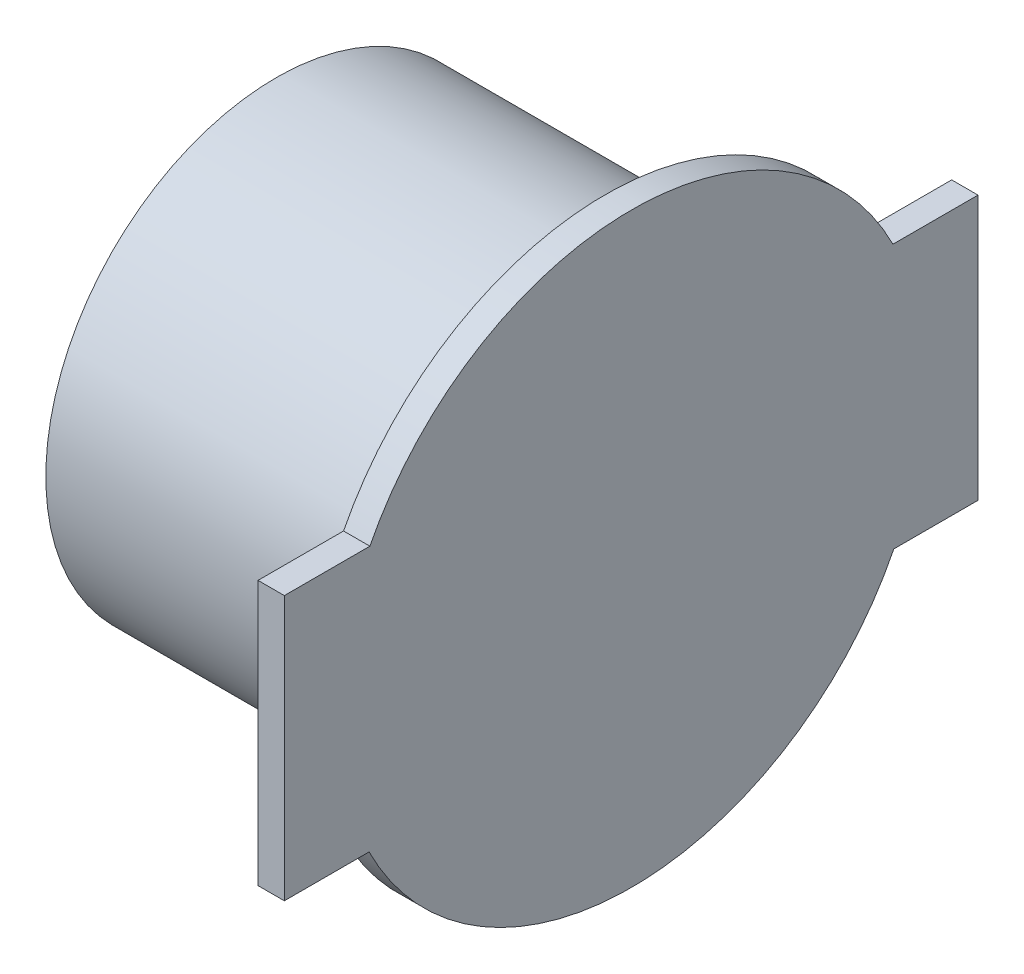
SolidWorks part; units mm, degrees
ref_plane "前视基准面" through (0, 0, 0) normal (0, 0, 1) x (1, 0, 0)
ref_plane "上视基准面" through (0, 0, 0) normal (0, 1, 0) x (1, 0, 0)
ref_plane "右视基准面" through (0, 0, 0) normal (1, 0, 0) x (0, 0, -1)
sketch "草图2" plane through (0, 0, 0) normal (1, 0, 0) x (0, 0, -1)
  circle A0 centre (0, 0) radius 17.5
extrude "凸台-拉伸1" add sketch "草图2" along normal blind 25
sketch "草图3" plane through (25, 0, 0) normal (1, 0, 0) x (0, 0, -1)
  line L0 (-22.2963, 10.1054) -> (-19.8748, 10.1054)
  line L3 (-22.2963, 10.1054) -> (-26.3749, 10.1054)
  line L4 (-26.3749, 0) -> (-26.3749, 10.1054)
  line L7 (-22.2963, -9.983) -> (-26.3749, -9.983)
  line L8 (-26.3749, 0) -> (-26.3749, -9.983)
  line L9 (-22.2963, -9.983) -> (-19.9366, -9.983)
  line L10 (19.9366, -9.983) -> (22.2963, -9.983)
  line L13 (22.2963, 10.1054) -> (26.3343, 10.1054)
  line L14 (26.3343, 0) -> (26.3343, 10.1054)
  line L17 (22.2963, -9.983) -> (26.3343, -9.983)
  line L18 (26.3343, 0) -> (26.3343, -9.983)
  line L19 (22.2963, 10.1054) -> (19.8748, 10.1054)
  arc A0 (-19.9366, -9.983) -> (19.9366, -9.983) centre (0, 0) ccw
  arc A1 (19.8748, 10.1054) -> (-19.8748, 10.1054) centre (0, 0) ccw
  point P6 (-22.2963, 0)
extrude "凸台-拉伸2" add sketch "草图3" along normal blind 2
